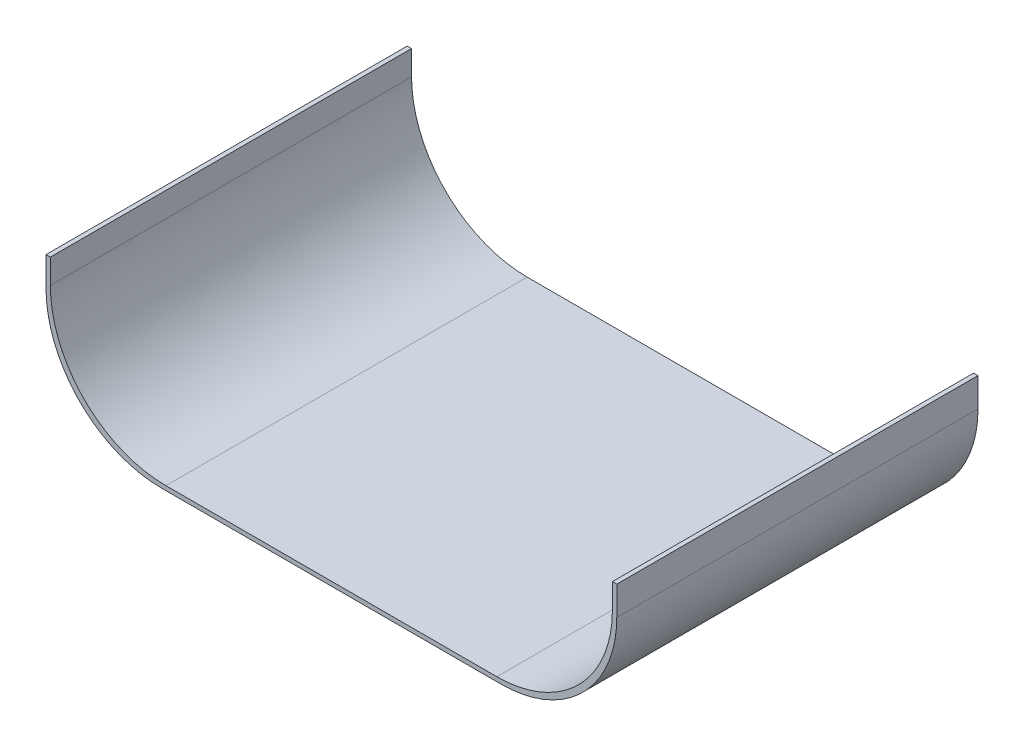
SolidWorks part; units mm, degrees
material "PPE"
ref_plane "Front Plane" through (0, 0, 0) normal (0, 0, 1) x (1, 0, 0)
ref_plane "Top Plane" through (0, 0, 0) normal (0, 1, 0) x (1, 0, 0)
ref_plane "Right Plane" through (0, 0, 0) normal (1, 0, 0) x (0, 0, -1)
sketch "Sketch1" plane through (0, 0, 0) normal (0, 1, 0) x (1, 0, 0)
  line L0 (197.5, 0) -> (197.5, 250)
  line L1 (0, 0) -> (395, 0) construction
  line L2 (0, 0) -> (0, 250) construction
  line L3 (0, 250) -> (395, 250) construction
  line L4 (395, 0) -> (395, 250) construction
  line L5 (0, 0) -> (395, 250) construction
  line L6 (0, 250) -> (395, 0) construction
  point P0 (0, 0)
  dimension "D1" = 395
  dimension "D2" = 250
sketch "Sketch4" plane through (0, 0, 0) normal (0, 0, 1) x (1, 0, 0)
  line L0 (0, 0) -> (0, -20)
  line L1 (80, -100) -> (315, -100)
  line L2 (395, -20) -> (395, 0)
  line L3 (0, 0) -> (3, 0)
  line L4 (0, 0) -> (395, 0) construction
  line L5 (3, 0) -> (3, -17)
  line L6 (83, -97) -> (312, -97)
  line L7 (392, -17) -> (392, 0)
  line L8 (392, 0) -> (395, 0)
  arc A0 (395, -20) -> (315, -100) centre (315, -20) cw
  arc A1 (80, -100) -> (0, -20) centre (80, -20) cw
  arc A2 (392, -17) -> (312, -97) centre (312, -17) cw
  arc A3 (83, -97) -> (3, -17) centre (83, -17) cw
  point P10 (0, -100)
  dimension "D2" = 80
  dimension "D6" = 80
  dimension "D1" = 100
  dimension "D3" = 3
  dimension "D4" = 3
  dimension "D5" = 3
sweep "Sweep1" add profiles "Sketch4" path "Sketch1"
